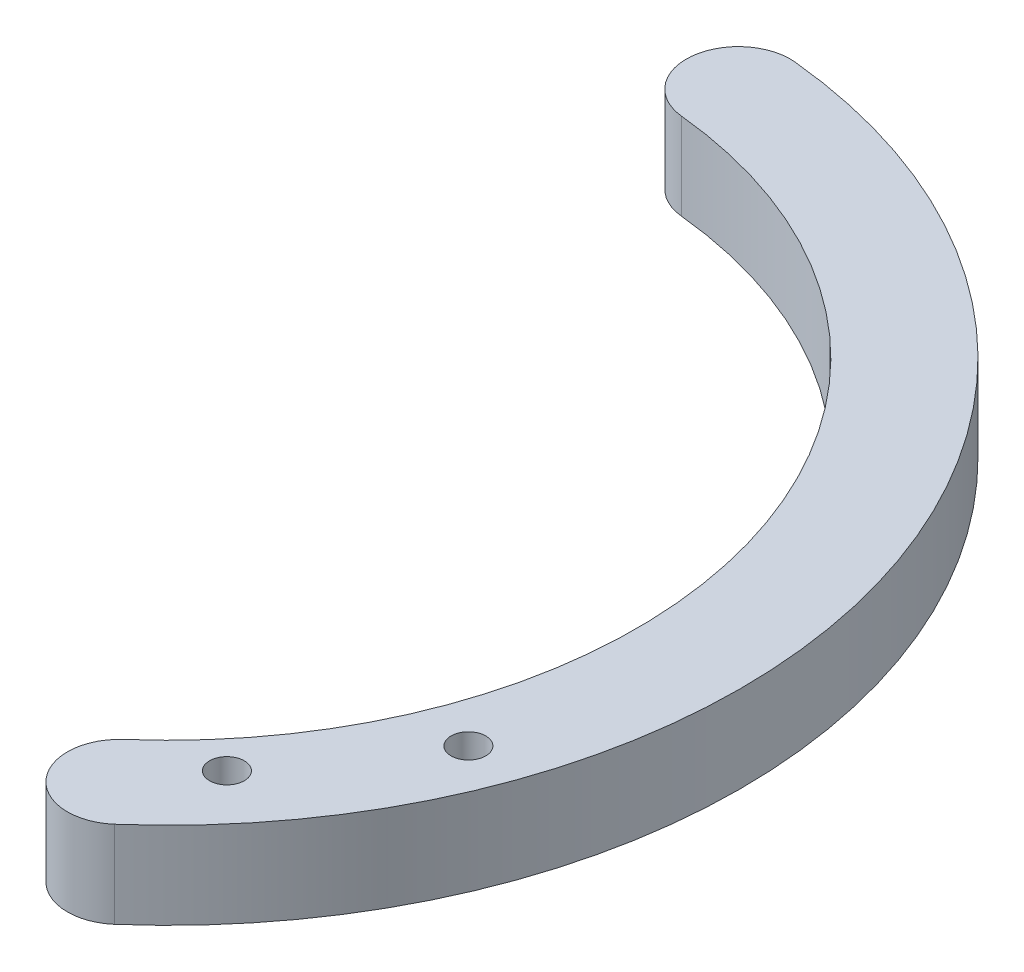
SolidWorks part; units mm, degrees
ref_plane "Front Plane" through (0, 0, 0) normal (0, 0, 1) x (1, 0, 0)
ref_plane "Top Plane" through (0, 0, 0) normal (0, 1, 0) x (1, 0, 0)
ref_plane "Right Plane" through (0, 0, 0) normal (1, 0, 0) x (0, 0, -1)
sketch "Sketch1" plane through (0, 0, 0) normal (0, 1, 0) x (1, 0, 0)
  line L0 (0, -55) -> (0, 55) construction
  line L1 (19.75, -22.5818) -> (28.0157, -10.7294) construction
  arc A0 (19.75, -22.5818) -> (3, 29.8496) centre (0, 0) ccw construction
  arc A1 (21.725, -24.84) -> (3.3, 32.8346) centre (0, 0) ccw
  arc A2 (17.775, -20.3236) -> (2.7, 26.8647) centre (0, 0) ccw
  arc A3 (17.775, -20.3236) -> (21.725, -24.84) centre (19.75, -22.5818) ccw
  arc A4 (3.3, 32.8346) -> (2.7, 26.8647) centre (3, 29.8496) ccw
  circle A6 centre (22.2955, -18.9317) radius 1
  circle A7 centre (28.0157, -10.7294) radius 1
  point P4 (28.5772, 9.1294)
  point P16 (32.4608, -39.061)
  dimension "D1" = 3
  dimension "D3" = 30
  dimension "D4" = 2
  dimension "D5" = 2
  dimension "D2" = 19.75
  dimension "D6" = 10
  dimension "D7" = 4.45
extrude "Boss-Extrude1" add sketch "Sketch1" along normal blind 5
